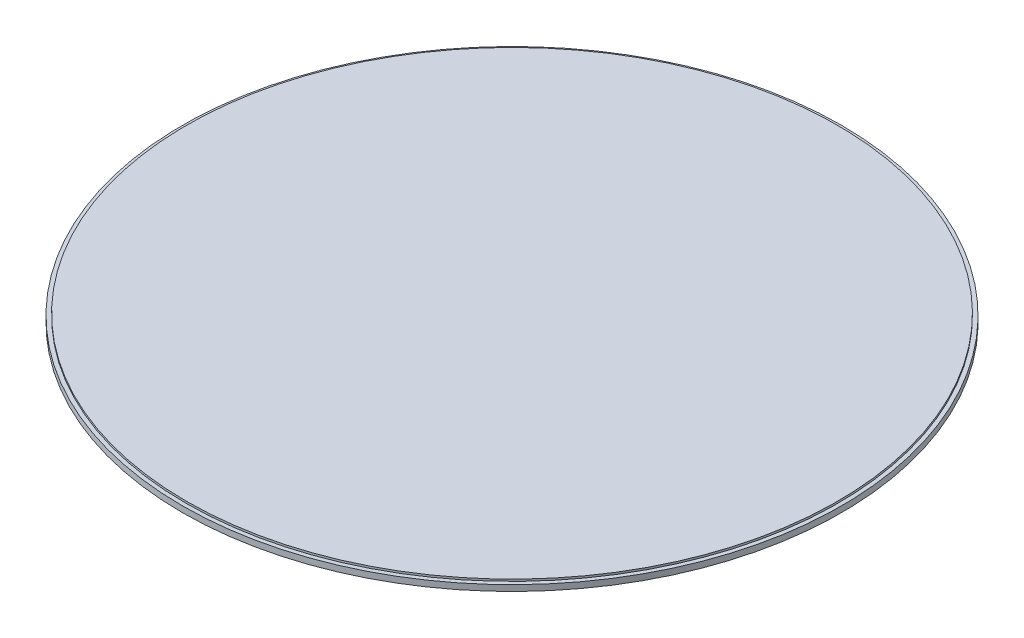
SolidWorks part; units mm, degrees
material "6061 Alloy"
ref_plane "Front Plane" through (0, 0, 0) normal (0, 0, 1) x (1, 0, 0)
ref_plane "Top Plane" through (0, 0, 0) normal (0, 1, 0) x (1, 0, 0)
ref_plane "Right Plane" through (0, 0, 0) normal (1, 0, 0) x (0, 0, -1)
sketch "Sketch1" plane through (0, 0, 0) normal (0, 1, 0) x (1, 0, 0)
  circle A0 centre (-46.3031, -6.6029) radius 42.55
  dimension "D1" = 85.1
extrude "Boss-Extrude1" add sketch "Sketch1" along normal blind 1
sketch "Sketch2" plane through (0, 1, 0) normal (0, 1, 0) x (1, 0, 0)
  circle A0 centre (-46.3031, -6.6029) radius 42.55
  circle A1 centre (-46.3031, -6.6029) radius 41.55
  dimension "D1" = 1
extrude "Cut-Extrude1" cut sketch "Sketch2" against normal through all
sketch "Sketch3" plane through (0, 1, 0) normal (0, 1, 0) x (1, 0, 0)
  circle A0 centre (-46.3031, -6.6029) radius 41.55
  circle A1 centre (-46.3031, -6.6029) radius 41.05
  dimension "D1" = 0.5
extrude "Cut-Extrude2" cut sketch "Sketch3" against normal blind 0.25
sketch "Sketch5" plane through (0, 1, 0) normal (0, 1, 0) x (1, 0, 0)
  circle A0 centre (-46.2874, -6.6307) radius 41.5819
  circle A1 centre (-46.2874, -6.6307) radius 41.5809
  dimension "D1" = 0.001
